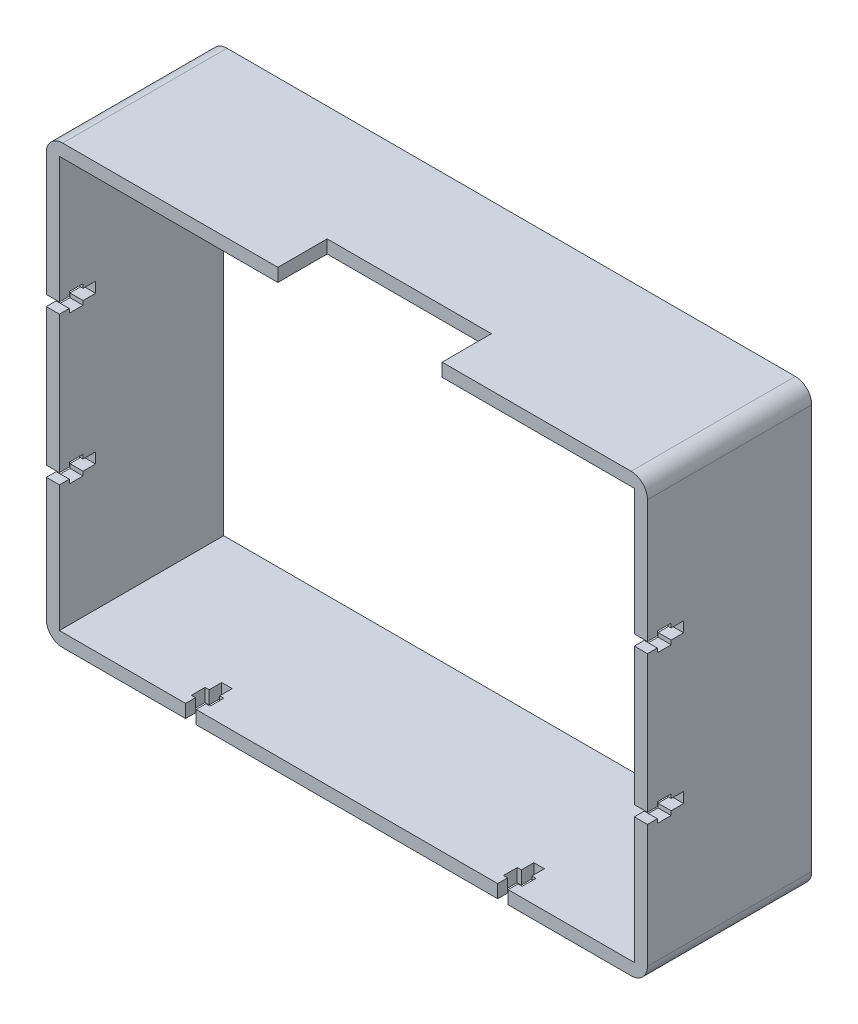
SolidWorks part; units mm, degrees
ref_plane "Plan de face" through (0, 0, 0) normal (0, 0, 1) x (1, 0, 0)
ref_plane "Plan de dessus" through (0, 0, 0) normal (0, 1, 0) x (1, 0, 0)
ref_plane "Plan de droite" through (0, 0, 0) normal (1, 0, 0) x (0, 0, -1)
sketch "Esquisse2" plane through (0, 0, 0) normal (0, 0, 1) x (1, 0, 0)
  line L0 (-85.9962, -62.5) -> (-87.5, -62.5)
  line L2 (87.5, -62.5) -> (87.5, 62.5)
  line L3 (87.5, 62.5) -> (-87.5, 62.5)
  line L4 (-87.5, -62.5) -> (-87.5, 62.5)
  line L5 (87.5, -62.5) -> (-87.5, 62.5) construction
  line L6 (87.5, 62.5) -> (-87.5, -62.5) construction
  line L8 (91.5, -66.5) -> (91.5, 66.5)
  line L9 (91.5, 66.5) -> (-91.5, 66.5)
  line L10 (-91.5, -66.5) -> (-91.5, 66.5)
  line L11 (91.5, -66.5) -> (-91.5, 66.5) construction
  line L12 (91.5, 66.5) -> (-91.5, -66.5) construction
  line L24 (-85.9962, -62.5) -> (87.5, -62.5)
  line L25 (91.5, -66.5) -> (-91.5, -66.5)
  point P0 (0, 0)
  point P6 (0, 0)
  dimension "D1" = 175
  dimension "D2" = 125
  dimension "D3" = 4
  dimension "D4" = 4
extrude "Boss.-Extru.2" add sketch "Esquisse2" along normal blind 50 contours L10 L9 L8 L25 | L4 L3 L2 L24 L0
sketch "Esquisse3" plane through (0, 66.5, 0) normal (0, 1, 0) x (1, 0, 0)
  line L0 (91.5, -50) -> (-91.5, -50) construction
  line L1 (29, -50) -> (-21, -50)
  line L2 (29, -50) -> (29, -35)
  line L3 (29, -35) -> (-21, -35)
  line L4 (-21, -50) -> (-21, -35)
  line L5 (91.5, -50) -> (91.5, 0) construction
  dimension "D1" = 50
  dimension "D2" = 62.5
  dimension "D3" = 15
extrude "Enlèv. mat.-Extru.1" cut sketch "Esquisse3" against normal blind 50
fillet "Congé1" radius 5 4 edges at (-91.5, 66.5, 25) (91.5, 66.5, 25) (91.5, -66.5, 25) (-91.5, -66.5, 25)
sketch "Esquisse4" plane through (0, 0, 50) normal (0, 0, 1) x (1, 0, 0)
  line L0 (87.5, -62.5) -> (87.5, 62.5) construction
  line L1 (86.5, -66.5) -> (-86.5, -66.5) construction
  line L2 (87.5, -62.5) -> (-87.5, -62.5) construction
  line L3 (0, -86.4168) -> (0, 98.3765) construction
  line L4 (-121.3986, 0) -> (121.7365, 0) construction
  circle A0 centre (89.5, -22.5) radius 1.6
  circle A1 centre (47.5, -64.5) radius 1.6
  circle A2 centre (-89.5, -22.5) radius 1.6
  circle A3 centre (-47.5, -64.5) radius 1.6
  circle A4 centre (-47.5, 64.5) radius 1.6
  circle A5 centre (-89.5, 22.5) radius 1.6
  circle A6 centre (47.5, 64.5) radius 1.6
  circle A7 centre (89.5, 22.5) radius 1.6
  dimension "D1" = 3.2
  dimension "D2" = 3.2
  dimension "D3" = 2
  dimension "D4" = 2
  dimension "D5" = 40
  dimension "D6" = 40
sketch "Esquisse6" plane through (91.5, 0, 0) normal (1, 0, 0) x (0, 0, -1)
  line L8 (-50, 20.9) -> (-47, 20.9)
  line L9 (-50, 20.9) -> (-50, 24.1)
  line L14 (-50, -20.9) -> (-50, -24.1) construction
  line L15 (-50, -24.1) -> (-47, -24.1)
  line L16 (-50, -24.1) -> (-50, -20.9)
  line L17 (-50, -20.9) -> (-47, -20.9)
  line L18 (-39, -24.1) -> (-39, -20.9)
  line L19 (-50, -86.4168) -> (-50, 98.3765) construction
  line L21 (-54, -24.1) -> (-50, -24.1) construction
  line L22 (-47, -20.9) -> (-47, -19.65)
  line L23 (-47, -25.35) -> (-42.8, -25.35)
  line L24 (-47, -25.35) -> (-47, -24.1)
  line L25 (-47, -19.65) -> (-42.8, -19.65)
  line L26 (-42.8, -25.35) -> (-42.8, -24.1)
  line L27 (-42.8, -24.1) -> (-39, -24.1)
  line L28 (-42.8, -20.9) -> (-42.8, -19.65)
  line L29 (-42.8, -20.9) -> (-39, -20.9)
  line L30 (-50, 24.1) -> (-47, 24.1)
  line L31 (-39, 20.9) -> (-39, 24.1)
  line L32 (-47, 24.1) -> (-47, 25.35)
  line L33 (-47, 19.65) -> (-42.8, 19.65)
  line L34 (-47, 19.65) -> (-47, 20.9)
  line L35 (-47, 25.35) -> (-42.8, 25.35)
  line L36 (-42.8, 19.65) -> (-42.8, 20.9)
  line L37 (-42.8, 20.9) -> (-39, 20.9)
  line L38 (-42.8, 24.1) -> (-42.8, 25.35)
  line L39 (-42.8, 24.1) -> (-39, 24.1)
  line L40 (-50, 24.1) -> (-50, 20.9) construction
  line L41 (-50, 24.1) -> (-54, 24.1) construction
  dimension "D2" = 11
  dimension "D3" = 3.2
  dimension "D4" = 5.7
  dimension "D5" = 1.25
  dimension "D6" = 4.2
  dimension "D7" = 3
  dimension "D8" = 0
  dimension "D9" = 0
  dimension "D10" = 11
  dimension "D11" = 3.2
  dimension "D12" = 0
  dimension "D13" = 5.7
  dimension "D14" = 1.25
  dimension "D15" = 4.2
  dimension "D16" = 3
extrude "Enlèv. mat.-Extru.3" cut sketch "Esquisse6" against normal blind 4
sketch "Esquisse7" plane through (-91.5, 0, 0) normal (-1, 0, 0) x (0, 0, 1)
  line L12 (47, 20.9) -> (50, 20.9)
  line L13 (47, 19.65) -> (47, 20.9)
  line L14 (42.8, 19.65) -> (47, 19.65)
  line L15 (42.8, 20.9) -> (42.8, 19.65)
  line L16 (39, 20.9) -> (42.8, 20.9)
  line L17 (39, 24.1) -> (39, 20.9)
  line L18 (42.8, 24.1) -> (39, 24.1)
  line L19 (42.8, 25.35) -> (42.8, 24.1)
  line L20 (47, 25.35) -> (42.8, 25.35)
  line L21 (47, 24.1) -> (47, 25.35)
  line L22 (50, 24.1) -> (47, 24.1)
  line L23 (50, 20.9) -> (50, 24.1)
  line L24 (47, 20.9) -> (50, 20.9)
  line L25 (47, 19.65) -> (47, 20.9)
  line L26 (42.8, 19.65) -> (47, 19.65)
  line L27 (42.8, 20.9) -> (42.8, 19.65)
  line L28 (39, 20.9) -> (42.8, 20.9)
  line L29 (39, 24.1) -> (39, 20.9)
  line L30 (42.8, 24.1) -> (39, 24.1)
  line L31 (42.8, 25.35) -> (42.8, 24.1)
  line L32 (47, 25.35) -> (42.8, 25.35)
  line L33 (47, 24.1) -> (47, 25.35)
  line L34 (50, 24.1) -> (47, 24.1)
  line L35 (50, 20.9) -> (50, 24.1)
  line L36 (47, -24.1) -> (50, -24.1)
  line L37 (50, -24.1) -> (50, -20.9)
  line L38 (50, -20.9) -> (47, -20.9)
  line L39 (47, -20.9) -> (47, -19.65)
  line L40 (47, -19.65) -> (42.8, -19.65)
  line L41 (42.8, -19.65) -> (42.8, -20.9)
  line L42 (42.8, -20.9) -> (39, -20.9)
  line L43 (39, -20.9) -> (39, -24.1)
  line L44 (39, -24.1) -> (42.8, -24.1)
  line L45 (42.8, -24.1) -> (42.8, -25.35)
  line L46 (42.8, -25.35) -> (47, -25.35)
  line L47 (47, -25.35) -> (47, -24.1)
  line L48 (47, -24.1) -> (50, -24.1)
  line L49 (50, -24.1) -> (50, -20.9)
  line L50 (50, -20.9) -> (47, -20.9)
  line L51 (47, -20.9) -> (47, -19.65)
  line L52 (47, -19.65) -> (42.8, -19.65)
  line L53 (42.8, -19.65) -> (42.8, -20.9)
  line L54 (42.8, -20.9) -> (39, -20.9)
  line L55 (39, -20.9) -> (39, -24.1)
  line L56 (39, -24.1) -> (42.8, -24.1)
  line L57 (42.8, -24.1) -> (42.8, -25.35)
  line L58 (42.8, -25.35) -> (47, -25.35)
  line L59 (47, -25.35) -> (47, -24.1)
  dimension "D1" = 0
  dimension "D2" = 0
extrude "Enlèv. mat.-Extru.4" cut sketch "Esquisse7" against normal blind 4
sketch "Esquisse9" plane through (0, -66.5, 0) normal (0, -1, 0) x (1, 0, 0)
  line L0 (-49.1, 50) -> (-45.9, 50)
  line L1 (-49.1, 50) -> (-49.1, 47)
  line L2 (-49.1, 39) -> (-45.9, 39)
  line L3 (-49.1, 42.8) -> (-50.35, 42.8)
  line L4 (-44.65, 42.8) -> (-45.9, 42.8)
  line L5 (-44.65, 42.8) -> (-44.65, 47)
  line L6 (-44.65, 47) -> (-45.9, 47)
  line L7 (-50.35, 42.8) -> (-50.35, 47)
  line L8 (-44.65, 42.8) -> (-50.35, 47) construction
  line L9 (-44.65, 47) -> (-50.35, 42.8) construction
  line L10 (-49.1, 47) -> (-50.35, 47)
  line L11 (-49.1, 42.8) -> (-49.1, 39)
  line L12 (-45.9, 42.8) -> (-45.9, 39)
  line L13 (-45.9, 50) -> (-45.9, 47)
  line L14 (-121.3986, 50) -> (121.7365, 50) construction
  line L15 (-49.1, 54) -> (-49.1, 50) construction
  line L16 (0, 61.3923) -> (0, 17.4924) construction
  line L17 (44.65, 47) -> (50.35, 42.8) construction
  line L18 (44.65, 42.8) -> (50.35, 47) construction
  line L19 (45.9, 50) -> (45.9, 47)
  line L20 (45.9, 42.8) -> (45.9, 39)
  line L21 (49.1, 42.8) -> (49.1, 39)
  line L22 (49.1, 47) -> (50.35, 47)
  line L23 (50.35, 42.8) -> (50.35, 47)
  line L24 (44.65, 47) -> (45.9, 47)
  line L25 (44.65, 42.8) -> (44.65, 47)
  line L26 (44.65, 42.8) -> (45.9, 42.8)
  line L27 (49.1, 42.8) -> (50.35, 42.8)
  line L28 (49.1, 39) -> (45.9, 39)
  line L29 (49.1, 50) -> (49.1, 47)
  line L30 (49.1, 50) -> (45.9, 50)
  point P4 (-47.5, 44.9)
  point P32 (47.5, 44.9)
  dimension "D1" = 3.2
  dimension "D2" = 5.7
  dimension "D3" = 4.2
  dimension "D4" = 3
  dimension "D5" = 1.25
  dimension "D6" = 1.25
  dimension "D7" = 1.25
  dimension "D8" = 3.8
  dimension "D9" = 11
  dimension "D10" = 0
  dimension "D11" = 0
extrude "Enlèv. mat.-Extru.5" cut sketch "Esquisse9" against normal blind 4
